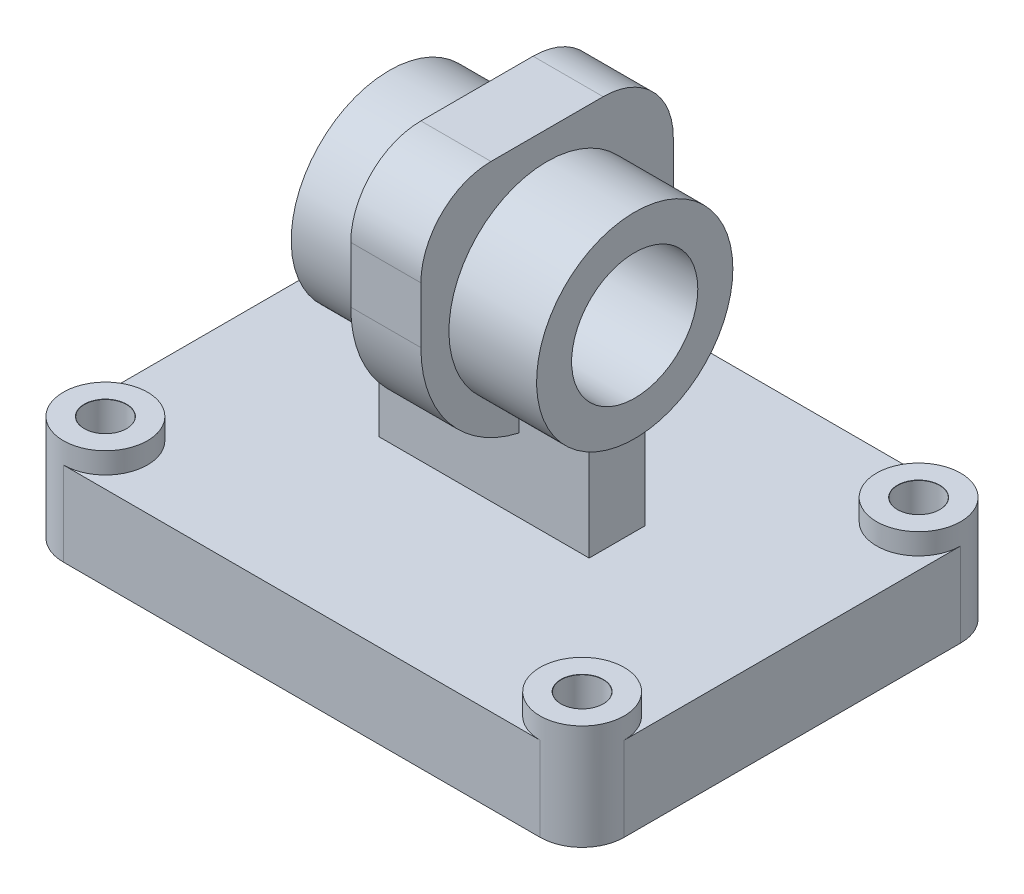
SolidWorks part; units mm, degrees
ref_plane "Front Plane" through (0, 0, 0) normal (0, 0, 1) x (1, 0, 0)
ref_plane "Top Plane" through (0, 0, 0) normal (0, 1, 0) x (1, 0, 0)
ref_plane "Right Plane" through (0, 0, 0) normal (1, 0, 0) x (0, 0, -1)
sketch "Sketch1" plane through (0, 0, 0) normal (0, 1, 0) x (1, 0, 0)
  line L1 (-34, 30) -> (34, 30)
  line L2 (-40, 24) -> (-40, -24)
  line L3 (-34, -30) -> (34, -30)
  line L4 (40, 24) -> (40, -24)
  line L5 (-40, 30) -> (40, -30) construction
  line L6 (-40, -30) -> (40, 30) construction
  arc A0 (-40, -24) -> (-34, -30) centre (-34, -24) ccw
  arc A1 (34, -30) -> (40, -24) centre (34, -24) ccw
  arc A2 (34, 30) -> (40, 24) centre (34, 24) cw
  arc A3 (-34, 30) -> (-40, 24) centre (-34, 24) ccw
  point P0 (0, 0)
  dimension "D3" = 6
  dimension "D1" = 60
  dimension "D2" = 80
extrude "Boss-Extrude1" add sketch "Sketch1" along normal blind 12
sketch "Sketch2" plane through (0, 12, 0) normal (0, 1, 0) x (1, 0, 0)
  circle A0 centre (-34, 24) radius 6
  circle A1 centre (-34, -24) radius 6
  circle A2 centre (34, 24) radius 6
  circle A3 centre (34, -24) radius 6
  arc A4 (-34, 30) -> (-40, 24) centre (-34, 24) ccw construction
  arc A5 (-40, -24) -> (-34, -30) centre (-34, -24) ccw construction
  arc A6 (40, 24) -> (34, 30) centre (34, 24) ccw construction
  arc A7 (34, -30) -> (40, -24) centre (34, -24) ccw construction
extrude "Boss-Extrude2" add sketch "Sketch2" along normal blind 3
sketch "Sketch3" plane through (0, 15, 0) normal (0, 1, 0) x (1, 0, 0)
  point P0 (-34, 24)
sketch "Sketch5" plane through (0, 15, 0) normal (0, 1, 0) x (1, 0, 0)
  point P0 (-34, 24)
  point P3 (34, 24)
  point P6 (34, -24)
  point P9 (-34, -24)
hole_wizard "Ø6.0 (6) Diameter Hole2" positions "Sketch5" profile "Sketch6" hole size "Ø6.0" standard "ANSI Metric" end condition through all
sketch "Sketch6" plane through (-34, 15, -24) normal (1, 0, 0) x (0, 0, 1)
  line L0 (0, 0) -> (0, 15)
  line L1 (0, 15) -> (3, 15)
  line L2 (3, 15) -> (3, 0.025)
  line L3 (3, 0.025) -> (3.025, 0)
  line L5 (3.025, 0) -> (0, 0)
  line L6 (-3, 0.025) -> (-3.025, 0) construction
  line L11 (0, -6.35) -> (0, 107.95) construction
  dimension "Thru Hole Dia." = 6
  dimension "Thru Hole Depth" = 15
  dimension "Near C'Sink Dia." = 6.05
  dimension "Near C'Sink Angle" = 90
sketch "Sketch7" plane through (0, 0, 0) normal (1, 0, 0) x (0, 0, -1)
  circle A0 centre (0, 40) radius 14
  circle A1 centre (0, 40) radius 9
  point P3 (0, 0)
  dimension "D1" = 28
  dimension "D2" = 18
  dimension "D3" = 40
extrude "Boss-Extrude4" add sketch "Sketch7" along normal mid plane 35 separate body
sketch "Sketch8" plane through (0, 0, 0) normal (1, 0, 0) x (0, 0, -1)
  line L0 (-18, 40) -> (-18, 58)
  line L1 (-18, 58) -> (18, 58)
  line L2 (18, 58) -> (18, 40)
  arc A0 (-18, 40) -> (18, 40) centre (0, 40) ccw
  circle A1 centre (0, 40) radius 14 construction
  circle A2 centre (0, 40) radius 14
  dimension "D1" = 36
extrude "Boss-Extrude6" add sketch "Sketch8" along normal mid plane 10 contours L1 L2 A0 L0
sketch "Sketch9" plane through (5, 0, 0) normal (1, 0, 0) x (0, 0, -1)
  circle A0 centre (0, 40) radius 9
extrude "Cut-Extrude1" cut sketch "Sketch9" against normal mid plane 60
sketch "Sketch10" plane through (0, 12, 0) normal (0, 1, 0) x (1, 0, 0)
  line L1 (-15, 4) -> (15, 4)
  line L2 (-15, 4) -> (-15, -4)
  line L3 (-15, -4) -> (15, -4)
  line L4 (15, 4) -> (15, -4)
  line L5 (-15, 4) -> (15, -4) construction
  line L6 (-15, -4) -> (15, 4) construction
  point P0 (0, 0)
  dimension "D1" = 8
  dimension "D2" = 30
extrude "Boss-Extrude7" add sketch "Sketch10" along normal up to body
fillet "Fillet1" radius 10 2 edges at (0, 58, 18) (0, 58, -18)
